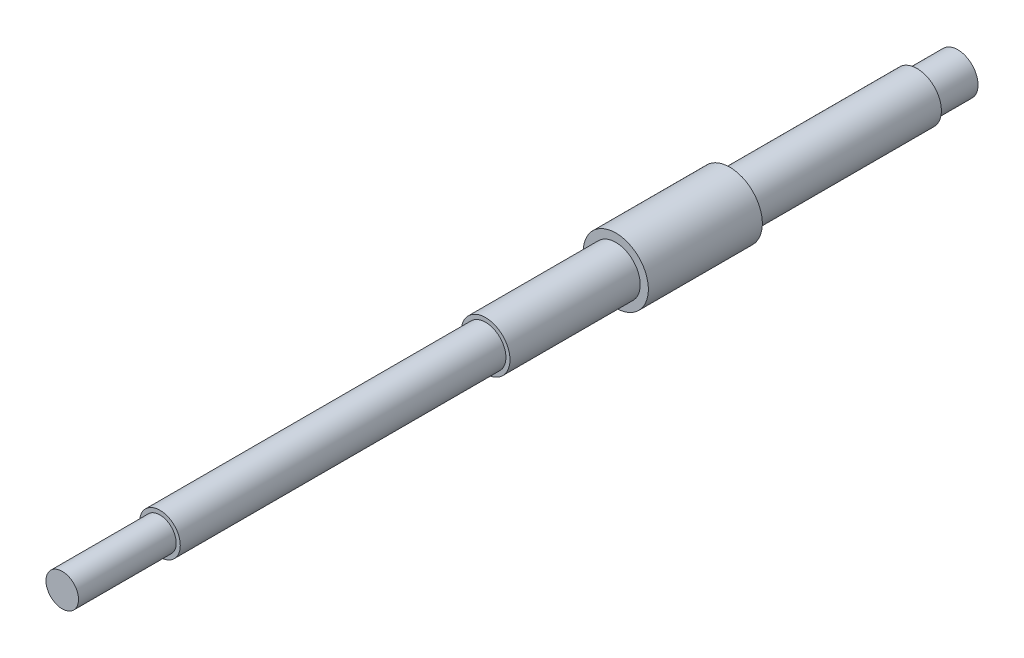
SolidWorks part; units mm, degrees
ref_plane "前视基准面" through (0, 0, 0) normal (0, 0, 1) x (1, 0, 0)
ref_plane "上视基准面" through (0, 0, 0) normal (0, 1, 0) x (1, 0, 0)
ref_plane "右视基准面" through (0, 0, 0) normal (1, 0, 0) x (0, 0, -1)
other "Configuration Table"
sketch "草图1" plane through (0, 0, 0) normal (0, 0, 1) x (1, 0, 0)
  circle A0 centre (0, 0) radius 3
  dimension "D1" = 6
extrude "凸台-拉伸1" add sketch "草图1" along normal blind 16
sketch "草图2" plane through (0, 0, 0) normal (0, 0, -1) x (-1, 0, 0)
  circle A0 centre (0, 0) radius 4
  dimension "D1" = 8
extrude "凸台-拉伸2" add sketch "草图2" along normal blind 14
sketch "草图3" plane through (0, 0, -14) normal (0, 0, -1) x (-1, 0, 0)
  circle A0 centre (0, 0) radius 3
  dimension "D1" = 6
extrude "凸台-拉伸3" add sketch "草图3" along normal blind 23
sketch "草图4" plane through (0, 0, 16) normal (0, 0, 1) x (1, 0, 0)
  circle A0 centre (0, 0) radius 2.5
  dimension "D1" = 5
extrude "凸台-拉伸4" add sketch "草图4" along normal blind 40
sketch "草图5" plane through (0, 0, -37) normal (0, 0, -1) x (-1, 0, 0)
  circle A0 centre (0, 0) radius 2.5
  dimension "D1" = 5
sketch "草图6" plane through (0, 0, 56) normal (0, 0, 1) x (1, 0, 0)
  circle A0 centre (0, 0) radius 1.5
  dimension "D1" = 3
sketch "草图7" plane through (0, 0, 56) normal (0, 0, 1) x (1, 0, 0)
  circle A0 centre (0, 0) radius 2
  dimension "D1" = 4
extrude "凸台-拉伸5" add sketch "草图7" along normal blind 12
extrude "凸台-拉伸6" add sketch "草图5" along normal blind 5 contours A0
